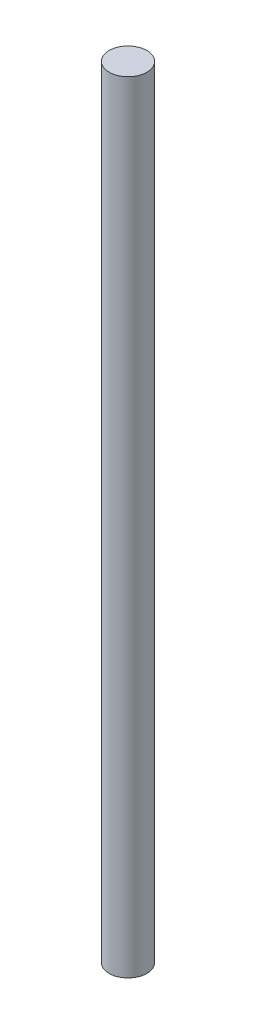
SolidWorks part; units mm, degrees
ref_plane "Front Plane" through (0, 0, 0) normal (0, 0, 1) x (1, 0, 0)
ref_plane "Top Plane" through (0, 0, 0) normal (0, 1, 0) x (1, 0, 0)
ref_plane "Right Plane" through (0, 0, 0) normal (1, 0, 0) x (0, 0, -1)
sketch "Sketch1" plane through (0, 0, 0) normal (0, 1, 0) x (1, 0, 0)
  circle A0 centre (0, 0) radius 88.9
  dimension "D1" = 177.8
extrude "Boss-Extrude1" add sketch "Sketch1" along normal blind 3683
